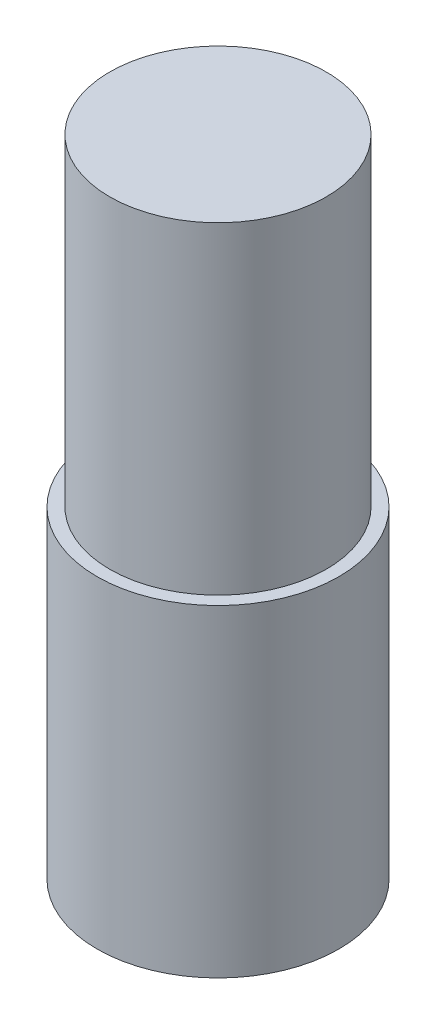
SolidWorks part; units mm, degrees
material "PUR"
ref_plane "Z" through (0, 0, 0) normal (0, 0, 1) x (1, 0, 0)
ref_plane "Y" through (0, 0, 0) normal (0, 1, 0) x (1, 0, 0)
ref_plane "X" through (0, 0, 0) normal (1, 0, 0) x (0, 0, -1)
sketch "Sketch1" plane through (0, 0, 0) normal (0, 1, 0) x (1, 0, 0)
  circle A0 centre (0, 0) radius 4.7625
  dimension "D1" = 9.525
extrude "Boss-Extrude1" add sketch "Sketch1" along normal blind 25.4
sketch "Sketch2" plane through (0, 25.4, 0) normal (0, 1, 0) x (1, 0, 0)
  circle A1 centre (0, 0) radius 6.3038
  circle A2 centre (0, 0) radius 4.2625
  circle A3 centre (0, 0) radius 4.2625
  dimension "D1" = 0.5
extrude "Cut-Extrude1" cut sketch "Sketch2" against normal blind 12.7
